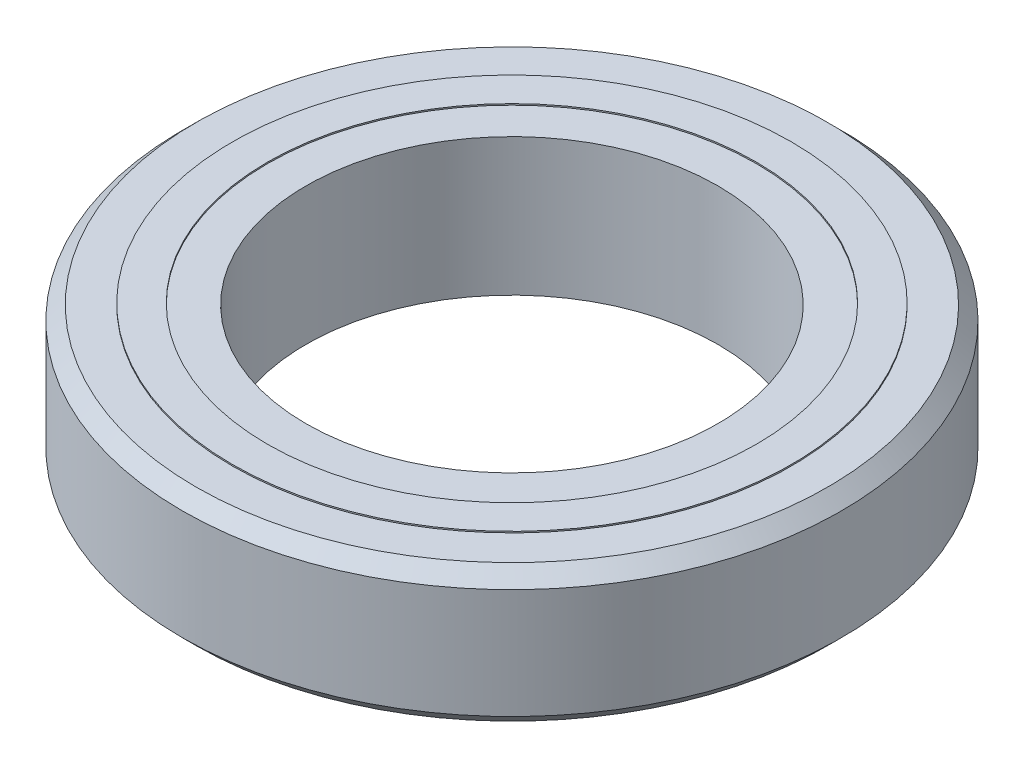
SolidWorks part; units mm, degrees
material "Acero aleado"
ref_plane "Alzado" through (0, 0, 0) normal (0, 0, 1) x (1, 0, 0)
ref_plane "Planta" through (0, 0, 0) normal (0, 1, 0) x (1, 0, 0)
ref_plane "Vista lateral" through (0, 0, 0) normal (1, 0, 0) x (0, 0, -1)
sketch "Croquis1" plane through (0, 0, 0) normal (0, 1, 0) x (1, 0, 0)
  circle A0 centre (0, 0) radius 7.5
  circle A1 centre (0, 0) radius 12
  dimension "D1" = 24
  dimension "D2" = 15
extrude "Saliente-Extruir1" add sketch "Croquis1" along normal mid plane 5
chamfer "Chaflán1" distance 0.5 angle 45 2 edges at (0, -2.5, 12) (0, 2.5, 12)
sketch "Croquis2" plane through (0, 0, 0) normal (0, 1, 0) x (1, 0, 0)
  circle A0 centre (0, 0) radius 8.9003
  circle A1 centre (0, 0) radius 10.1756
extrude "Saliente-Extruir2" add sketch "Croquis2" along normal mid plane 5.1
